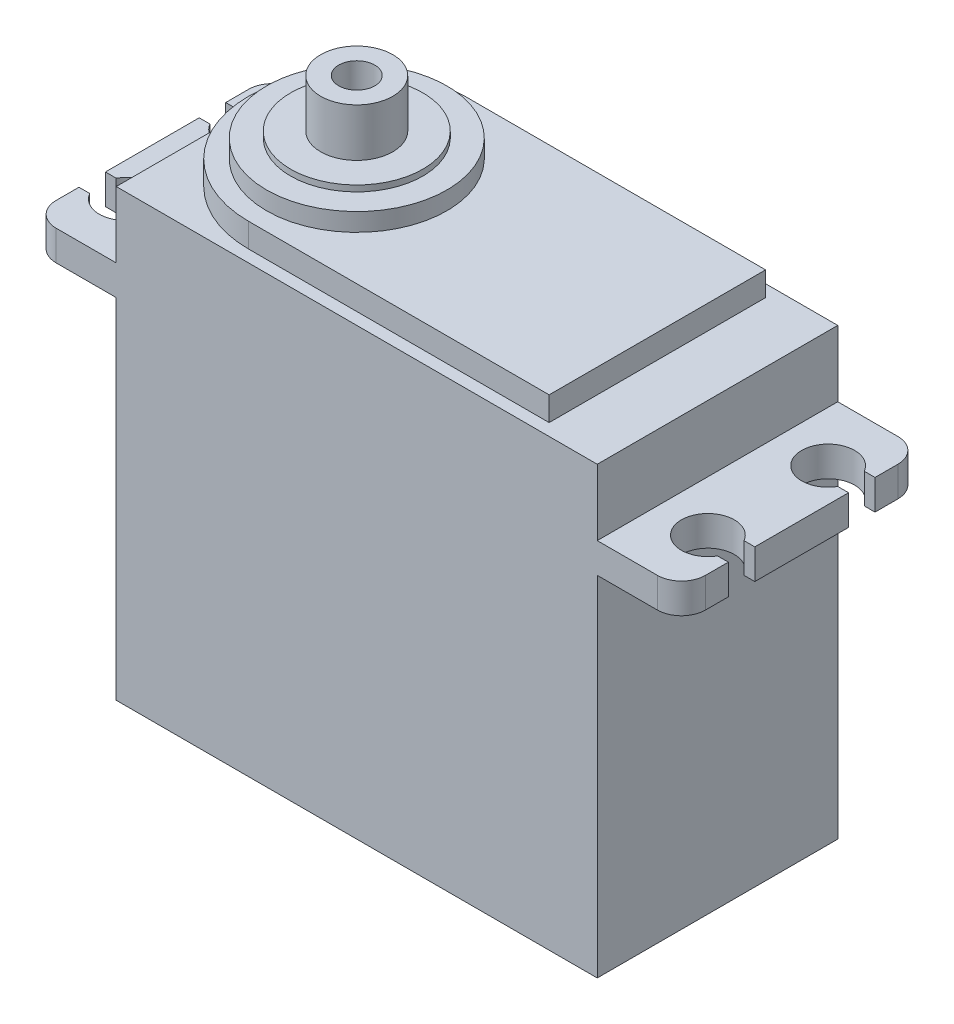
SolidWorks part; units mm, degrees
material "POM 乙缩醛共聚物"
ref_plane "前视基准面" through (0, 0, 0) normal (0, 0, 1) x (1, 0, 0)
ref_plane "上视基准面" through (0, 0, 0) normal (0, 1, 0) x (1, 0, 0)
ref_plane "右视基准面" through (0, 0, 0) normal (1, 0, 0) x (0, 0, -1)
sketch "草图1" plane through (0, 0, 0) normal (0, 1, 0) x (1, 0, 0)
  line L1 (-20, -10) -> (20, -10)
  line L2 (-20, -10) -> (-20, 10)
  line L3 (-20, 10) -> (20, 10)
  line L4 (20, -10) -> (20, 10)
  line L5 (-20, -10) -> (20, 10) construction
  line L6 (-20, 10) -> (20, -10) construction
  point P0 (0, 0)
  dimension "D1" = 40
  dimension "D2" = 20
extrude "凸台-拉伸1" add sketch "草图1" along normal blind 37
ref_plane "基准面1" through (0, 29, 0) normal (0, -1, 0) x (-1, 0, 0)
sketch "草图2" plane through (0, 29, 0) normal (0, -1, 0) x (-1, 0, 0)
  line L1 (27, -10) -> (-27, -10)
  line L2 (27, -10) -> (27, 10)
  line L3 (27, 10) -> (-27, 10)
  line L4 (-27, -10) -> (-27, 10)
  line L5 (27, -10) -> (-27, 10) construction
  line L6 (27, 10) -> (-27, -10) construction
  point P0 (0, 0)
  dimension "D1" = 54
  dimension "D2" = 20
extrude "凸台-拉伸2" add sketch "草图2" against normal blind 2.5
sketch "草图3" plane through (0, 29, 0) normal (0, -1, 0) x (-1, 0, 0)
  line L0 (0, 0) -> (30.7764, 0) construction
  line L1 (0, 14.376) -> (0, -16.6057) construction
  line L2 (-24.2, 5) -> (24.2, 5) construction
  circle A0 centre (24.2, 5) radius 2.2
  circle A1 centre (-24.2, 5) radius 2.2
  circle A2 centre (24.2, -5) radius 2.2
  circle A3 centre (-24.2, -5) radius 2.2
  dimension "D1" = 4.4
  dimension "D2" = 48.4
  dimension "D3" = 10
extrude "切除-拉伸1" cut sketch "草图3" against normal blind 2.5
sketch "草图5" plane through (0, 29, 0) normal (0, -1, 0) x (-1, 0, 0)
  line L0 (-24.2, 5) -> (24.2, 5) construction
  line L1 (0, 14.1298) -> (0, -13.2316) construction
  line L2 (-27, 6.1) -> (-25.5, 6.1)
  line L3 (-27, 10) -> (-27, -10) construction
  line L4 (-25.5, 6.1) -> (-25.5, 3.9)
  line L5 (-25.5, 3.9) -> (-27, 3.9)
  line L6 (-27, 3.9) -> (-27, 6.1)
  line L7 (27, 3.9) -> (27, 6.1)
  line L8 (25.5, 3.9) -> (27, 3.9)
  line L9 (25.5, 6.1) -> (25.5, 3.9)
  line L10 (27, 6.1) -> (25.5, 6.1)
  line L11 (-28.6426, 0) -> (33.6245, 0) construction
  line L12 (25.5, -6.1) -> (25.5, -3.9)
  line L13 (25.5, -3.9) -> (27, -3.9)
  line L14 (27, -3.9) -> (27, -6.1)
  line L15 (27, -6.1) -> (25.5, -6.1)
  line L16 (-25.5, -3.9) -> (-27, -3.9)
  line L17 (-27, -3.9) -> (-27, -6.1)
  line L18 (-25.5, -6.1) -> (-25.5, -3.9)
  line L19 (-27, -6.1) -> (-25.5, -6.1)
  dimension "D1" = 2.2
  dimension "D2" = 1.5
extrude "切除-拉伸2" cut sketch "草图5" against normal blind 2.5
fillet "圆角1" radius 2 4 edges at (27, 30.25, 10) (27, 30.25, -10) (-27, 30.25, 10) (-27, 30.25, -10)
sketch "草图6" plane through (0, 37, 0) normal (0, 1, 0) x (1, 0, 0)
  line L0 (-19.0995, 0) -> (19.3929, 0) construction
  line L1 (-27, -3.9) -> (-27, 3.9) construction
  line L2 (-10, 9) -> (15, 9)
  line L3 (15, 9) -> (15, -9)
  line L4 (15, -9) -> (-10, -9)
  arc A1 (-10, 9) -> (-10, -9) centre (-10, 0) ccw
  dimension "D1" = 17
  dimension "D2" = 9
  dimension "D3" = 15
extrude "凸台-拉伸3" add sketch "草图6" along normal blind 2
sketch "草图7" plane through (0, 39, 0) normal (0, 1, 0) x (1, 0, 0)
  line L0 (-16.7618, 0) -> (14.4634, 0) construction
  line L1 (0, 7.0403) -> (0, -7.5202) construction
  circle A0 centre (-10, 0) radius 7.5
  dimension "D1" = 15
  dimension "D2" = 10
extrude "凸台-拉伸4" add sketch "草图7" along normal blind 1.5
sketch "草图8" plane through (0, 40.5, 0) normal (0, 1, 0) x (1, 0, 0)
  line L0 (-12.6246, 0) -> (13.3069, 0) construction
  line L1 (0, 7.6879) -> (0, -7.8504) construction
  circle A0 centre (-10, 0) radius 5.5
extrude "凸台-拉伸5" add sketch "草图8" along normal blind 0.5
sketch "草图9" plane through (0, 41, 0) normal (0, 1, 0) x (1, 0, 0)
  line L0 (-10.8865, 0) -> (12.7935, 0) construction
  circle A0 centre (-10, 0) radius 3
  dimension "D1" = 6
extrude "凸台-拉伸6" add sketch "草图9" along normal blind 4
sketch "草图10" plane through (0, 45, 0) normal (0, 1, 0) x (1, 0, 0)
  circle A0 centre (-10, 0) radius 1.5
  dimension "D1" = 3
extrude "切除-拉伸3" cut sketch "草图10" against normal blind 5
